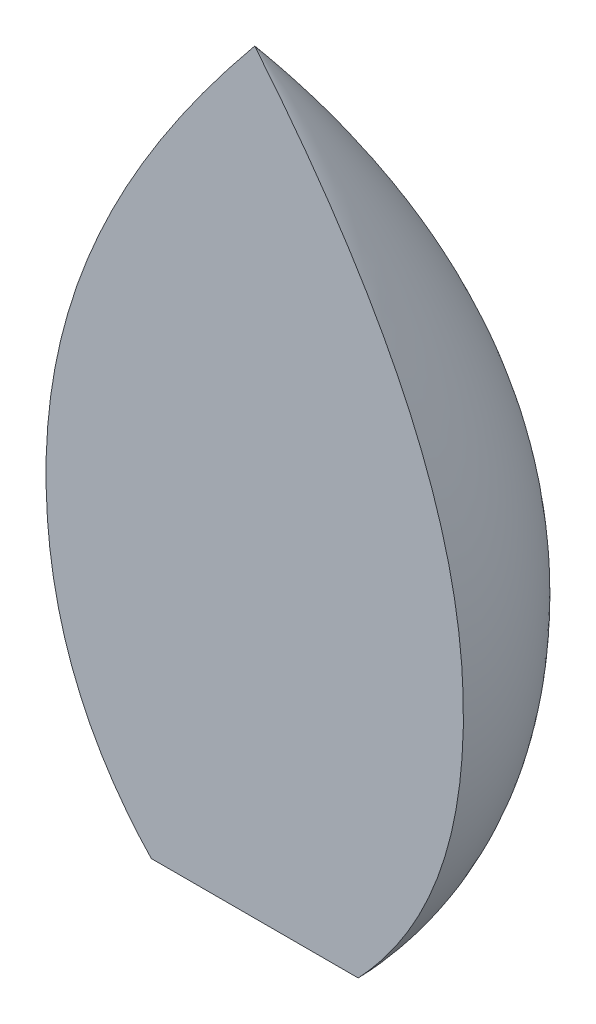
SolidWorks part; units mm, degrees
ref_plane "前视基准面" through (0, 0, 0) normal (0, 0, 1) x (1, 0, 0)
ref_plane "上视基准面" through (0, 0, 0) normal (0, 1, 0) x (1, 0, 0)
ref_plane "右视基准面" through (0, 0, 0) normal (1, 0, 0) x (0, 0, -1)
sketch "草图2" plane through (0, 0, 0) normal (0, 0, 1) x (1, 0, 0)
  line L0 (0, 0) -> (0, 50)
  line L1 (0, 0) -> (0, -23)
  line L2 (0, 0) -> (41.2304, 0)
  line L3 (0, -23) -> (10, -23)
  line L5 (2, -23) -> (3.1779, 46) construction
  line L6 (2.3758, -0.9867) -> (19.8758, -1.2854) construction
  spline S0 degree 3 poles (0, 50) (15.2885, 31.3934) (21.1053, 14.2462) (19.266, -10.5504) (14.2499, -18.4992) (10, -23) knots 0 0 0 0 0.506987 0.606987 1 1 1 1
  dimension "D8" = 22.0133
  dimension "D1" = 50
  dimension "D2" = 10
  dimension "D3" = 20
  dimension "D4" = 23
  dimension "D5" = 2
  dimension "D6" = 69
  dimension "D7" = 17.5
revolve "旋转1" add sketch "草图2" angle 180 about L0
